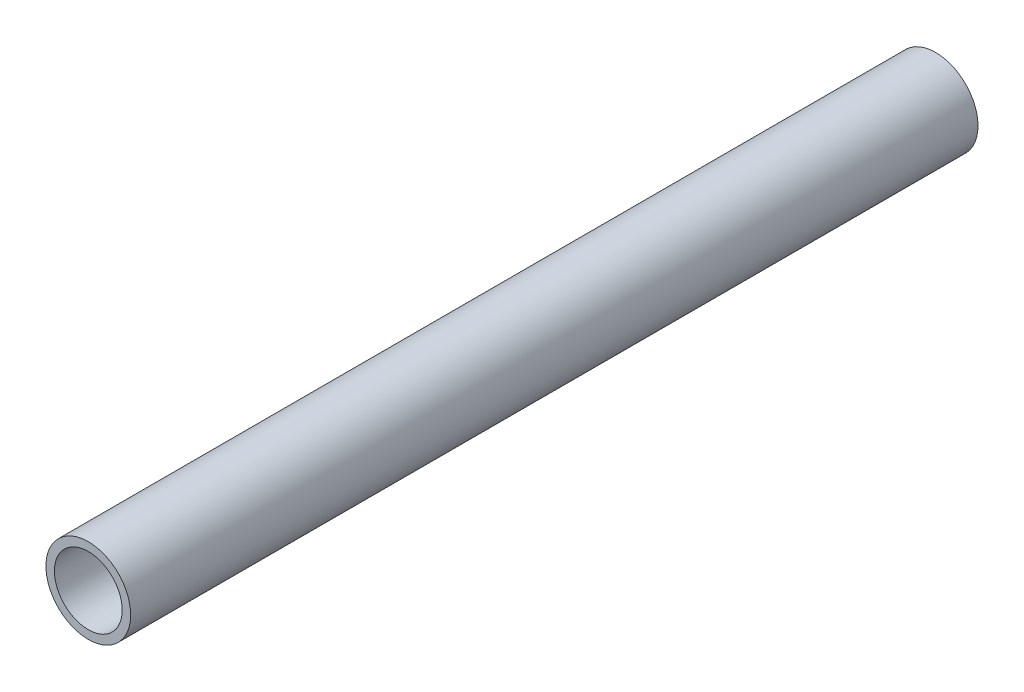
SolidWorks part; units mm, degrees
material "Thornel Mat VMA"
ref_plane "Płaszczyzna przednia" through (0, 0, 0) normal (0, 0, 1) x (1, 0, 0)
ref_plane "Płaszczyzna górna" through (0, 0, 0) normal (0, 1, 0) x (1, 0, 0)
ref_plane "Płaszczyzna prawa" through (0, 0, 0) normal (1, 0, 0) x (0, 0, -1)
sketch "Szkic1" plane through (0, 0, 0) normal (0, 0, 1) x (1, 0, 0)
  circle A0 centre (0, 0) radius 8
  circle A1 centre (0, 0) radius 10
  dimension "D1" = 2
  dimension "D2" = 20
extrude "Dodanie-wyciągnięcie1" add sketch "Szkic1" along normal blind 200
